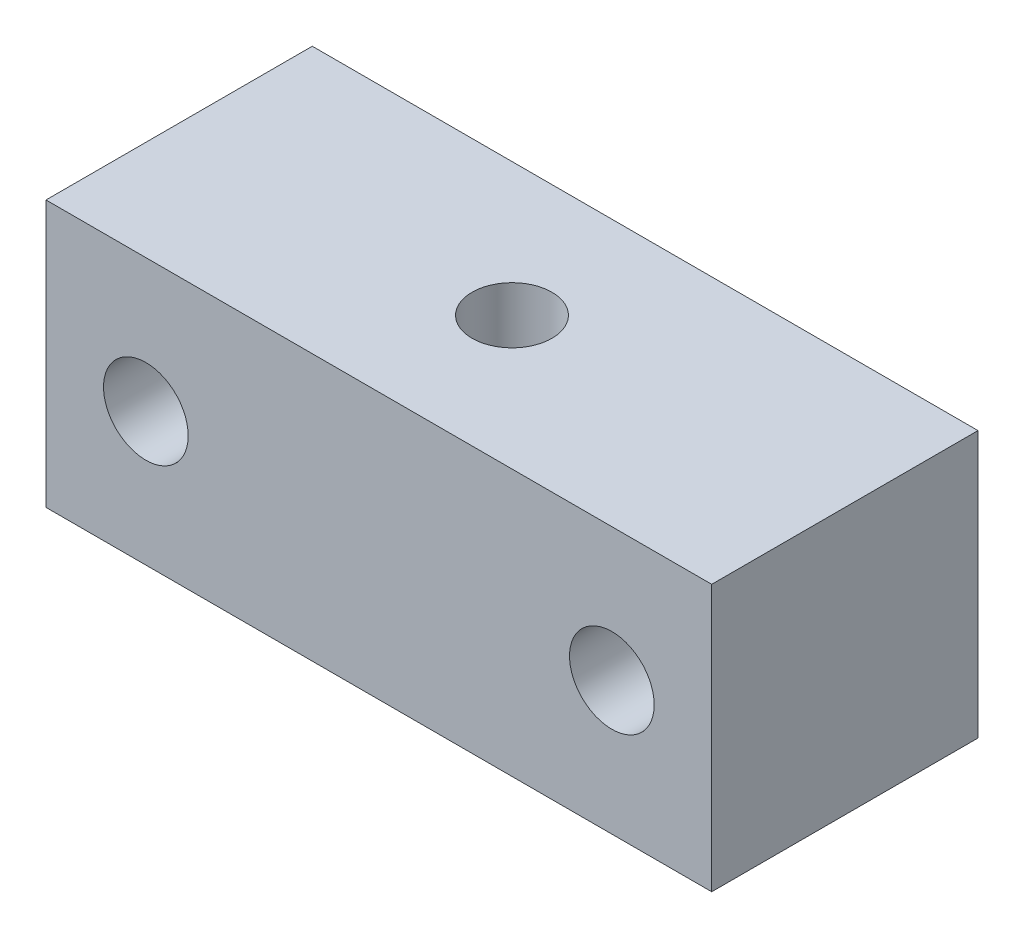
SolidWorks part; units mm, degrees
material "6061-T6 (SS)"
ref_plane "Front Plane" through (0, 0, 0) normal (0, 0, 1) x (1, 0, 0)
ref_plane "Top Plane" through (0, 0, 0) normal (0, 1, 0) x (1, 0, 0)
ref_plane "Right Plane" through (0, 0, 0) normal (1, 0, 0) x (0, 0, -1)
sketch "Sketch1" plane through (0, 0, 0) normal (0, 0, 1) x (1, 0, 0)
  line L1 (0, 0) -> (31.75, 0)
  line L2 (0, 0) -> (0, 12.7)
  line L3 (0, 12.7) -> (31.75, 12.7)
  line L4 (31.75, 0) -> (31.75, 12.7)
  dimension "D1" = 12.7
  dimension "D2" = 31.75
extrude "Boss-Extrude1" add sketch "Sketch1" along normal mid plane 12.7
sketch "Sketch2" plane through (0, 0, 6.35) normal (0, 0, 1) x (1, 0, 0)
  line L0 (0, 6.35) -> (31.75, 6.35) construction
  line L1 (0, 12.7) -> (0, 0) construction
  line L2 (31.75, 0) -> (31.75, 12.7) construction
  circle A0 centre (4.7625, 6.35) radius 2.0193
  circle A1 centre (26.9875, 6.35) radius 2.0193
  dimension "D1" = 4.0386
  dimension "D2" = 4.7625
  dimension "D3" = 4.7625
extrude "Cut-Extrude1" cut sketch "Sketch2" against normal through all
sketch "Sketch3" plane through (0, 12.7, 0) normal (0, 1, 0) x (1, 0, 0)
  line L0 (15.875, 6.35) -> (15.875, -6.35) construction
  line L1 (31.75, 6.35) -> (0, 6.35) construction
  line L2 (31.75, -6.35) -> (0, -6.35) construction
  circle A0 centre (15.875, 0) radius 1.905
  dimension "D1" = 3.81
extrude "Cut-Extrude2" cut sketch "Sketch3" against normal through all
equation "\"D3@Sketch2\"=\"D2@Sketch2\""
